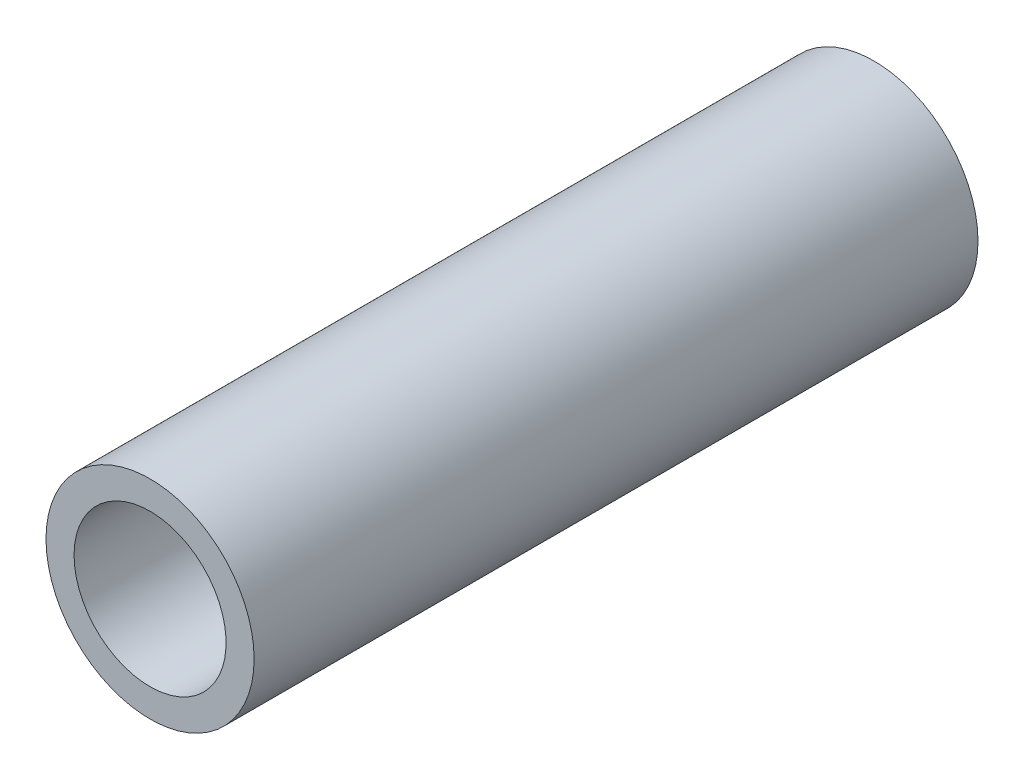
SolidWorks part; units mm, degrees
ref_plane "Front Plane" through (0, 0, 0) normal (0, 0, 1) x (1, 0, 0)
ref_plane "Top Plane" through (0, 0, 0) normal (0, 1, 0) x (1, 0, 0)
ref_plane "Right Plane" through (0, 0, 0) normal (1, 0, 0) x (0, 0, -1)
ref_plane "Plane1" through (0, 0, -40) normal (0, 0, -1) x (-1, 0, 0)
sketch "Sketch2" plane through (0, 0, -40) normal (0, 0, -1) x (-1, 0, 0)
  circle A0 centre (0, 0) radius 4.2
  circle A1 centre (0, 0) radius 5.75
  dimension "D1" = 8.4
  dimension "D2" = 11.5
extrude "Boss-Extrude1" add sketch "Sketch2" along normal blind 40
